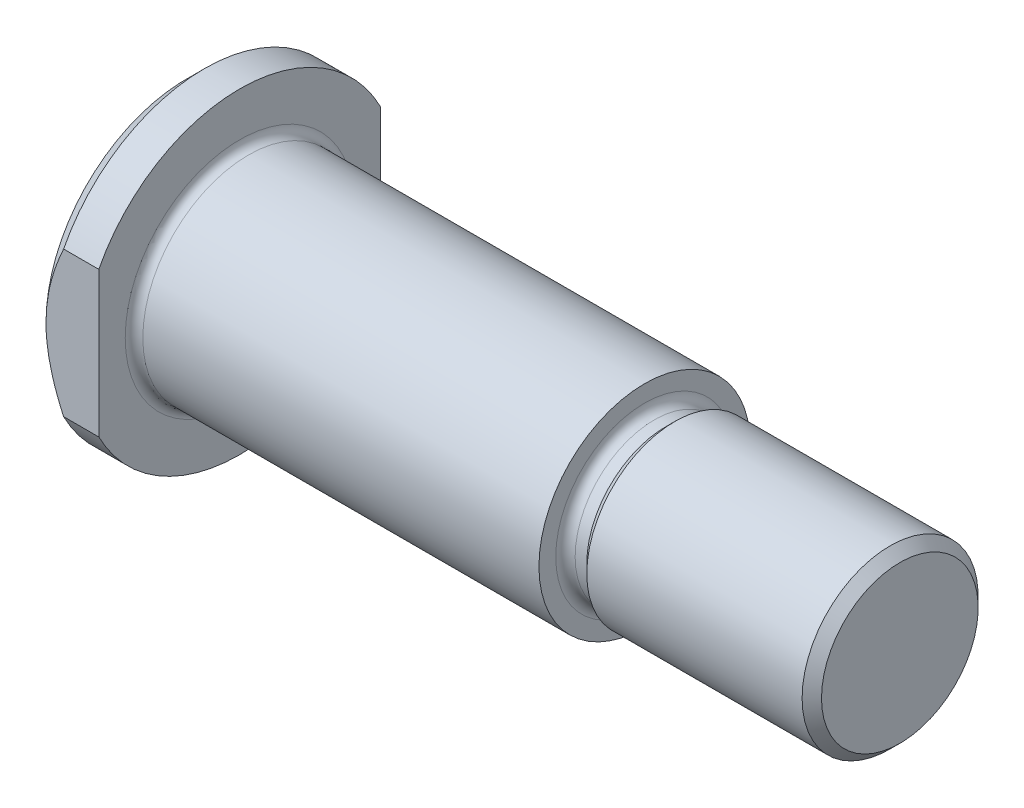
SolidWorks part; units mm, degrees
ref_plane "Plane1" through (0, 0, 0) normal (0, 0, 1) x (1, 0, 0)
ref_plane "Plane2" through (0, 0, 0) normal (0, 1, 0) x (1, 0, 0)
ref_plane "Plane3" through (0, 0, 0) normal (1, 0, 0) x (0, 0, -1)
sketch "BodySke" plane through (0, 0, 0) normal (0, 0, 1) x (1, 0, 0)
  line L0 (0, 0) -> (0, 16)
  line L1 (0, 16) -> (2, 18)
  line L2 (2, 18) -> (6, 18)
  line L3 (6, 18) -> (6, 12)
  line L6 (6, 12) -> (52, 12)
  line L7 (52, 12) -> (52, 10.089)
  line L8 (53.1015, 8.9875) -> (54.4233, 8.9875)
  line L9 (54.4233, 8.9875) -> (55.4358, 10)
  line L10 (55.4358, 10) -> (79.8985, 10)
  line L11 (79.8985, 10) -> (81, 8.8985)
  line L12 (81, 8.8985) -> (81, 0)
  line L13 (81, 0) -> (0, 0)
  line L14 (-6.35, 0) -> (107.95, 0) construction
  line L20 (56.4233, 13.8389) -> (56.4233, -3.5139) construction
  line L21 (53.6522, 12.6746) -> (53.6523, -3.175) construction
  arc A0 (52, 10.089) -> (53.1015, 8.9875) centre (53.1015, 10.089) ccw
  point P29 (52, 8.9875)
  dimension "D2" = 1.1015
  dimension "Head_ht" = 6
  dimension "D11" = 45
  dimension "Thread_length" = 29
  dimension "Thread_neck_width" = 2.4233
  dimension "Thread_nom" = 27.3478
  dimension "Advance" = 2
  dimension "Thread_lim" = 24.5767
  dimension "Head_dia" = 36
  dimension "Length" = 75
  dimension "D3" = 17.975
  dimension "D4" = 45
  dimension "HeadChHt" = 2
  dimension "D5" = 45
  dimension "Diameter" = 24
  dimension "Thread_dia" = 20
  dimension "Minor_dia" = 17.797
revolve "BaseBody" add sketch "BodySke" angle 360 about L14
cosmetic thread "ThreadCosmetic" [suppressed] parameters "Thread_length"=24.5767, "Thread_minor"=17.797
sketch "Sketch1" plane through (0, 0, 0) normal (-1, 0, 0) x (0, 0, 1)
  line L1 (-16, -18) -> (-18, -18)
  line L2 (-16, -18) -> (-16, 18)
  line L3 (-16, 18) -> (-18, 18)
  line L4 (-18, -18) -> (-18, 18)
  line L5 (18, -18) -> (16, -18)
  line L6 (18, -18) -> (18, 18)
  line L7 (18, 18) -> (16, 18)
  line L8 (16, -18) -> (16, 18)
  dimension "D1" = 36
  dimension "D2" = 18
  dimension "WidthFlats" = 32
  dimension "D3" = 16
  dimension "D4" = 36
  dimension "D5" = 18
extrude "Cut-Extrude1" cut sketch "Sketch1" against normal up to surface (6 mm away)
fillet "Fillet1" radius 1 1 edges at (6, 0, 12)
sketch "ThdSchSke" plane through (0, 0, 0) normal (0, 0, 1) x (1, 0, 0)
  line L0 (56.4233, -8.8985) -> (54.2516, -12)
  line L1 (56.4233, -8.8985) -> (58.595, -12)
  line L2 (58.595, -12) -> (58.595, -15)
  line L3 (-3.175, 0) -> (5.1513, 0) construction
  line L5 (58.595, -15) -> (54.2516, -15)
  line L6 (54.2516, -15) -> (54.2516, -12)
  dimension "Thread_minor" = 17.797
  dimension "Diameter" = 24
  dimension "SideAngle" = 55
  dimension "VeeAngle" = 70
  dimension "Overcut" = 30
  dimension "Start" = 56.4233
revolve "ThreadSchematic" [suppressed] cut sketch "ThdSchSke" angle 360 about L3
pattern_linear "ThdSchPat" [suppressed]
equation "\"Thread_minor@ThreadCosmetic\" = \"Minor_dia@BodySke\""
equation "\"Thread_length@ThreadCosmetic\" = ((sgn( (\"Thread_length@BodySke\" - \"Advance@BodySke\" - \"Thread_neck_width@BodySke\" ) - \"Thread_nom@BodySke\" )-1)*( (\"Thread_length@BodySke\" - \"Advance@BodySke\" - \"Thread_neck_width@BodySke\" ) - \"Thread_nom@BodySke\" ))/-2+ \"Thread_nom@BodySke\""
equation "\"Thread_minor@ThdSchSke\" = \"Minor_dia@BodySke\""
equation "\"Diameter@ThdSchSke\" = \"Diameter@BodySke\""
equation "\"Overcut@ThdSchSke\" = \"Diameter@BodySke\" * 1.25"
equation "\"Start@ThdSchSke\" = \"Head_ht@BodySke\" + \"Length@BodySke\" -  \"Thread_length@ThreadCosmetic\"  '---Non-countersunk---"
equation "\"Num_threads@ThdSchPat\" = int( \"Thread_length@ThreadCosmetic\" / \"Advance@BodySke\" + 0.999 ) + 1"
equation "\"Advance@ThdSchPat\" = \"Thread_length@ThreadCosmetic\" /  (\"Num_threads@ThdSchPat\" - 1) 'relax it"
equation "\"Num_threads@ThdSchPat\" = \"Num_threads@ThdSchPat\" - sgn( \"Num_threads@ThdSchPat\" - 1) '---chamfered tips only---"
equation "\"D3@BodySke\" = \"Minor_dia@BodySke\" * 1.01"
equation "\"D2@BodySke\" = (\"Thread_dia@BodySke\" - \"Minor_dia@BodySke\") / 2"
equation "\"Thread_neck_width@BodySke\" =  ( \"Thread_dia@BodySke\" - \"Minor_dia@BodySke\" )  * 1.1"
equation "\"Thread_nom@BodySke\" = \"Thread_length@BodySke\" - \"D2@BodySke\" * 1.5"
equation "\"D1@Sketch1\" = \"Head_dia@BodySke\""
equation "\"D2@Sketch1\" = \"D1@Sketch1\" / 2"
equation "\"D3@Sketch1\" = \"WidthFlats@Sketch1\" / 2"
equation "\"D4@Sketch1\" = \"D1@Sketch1\""
equation "\"D5@Sketch1\" = \"D4@Sketch1\" / 2"
